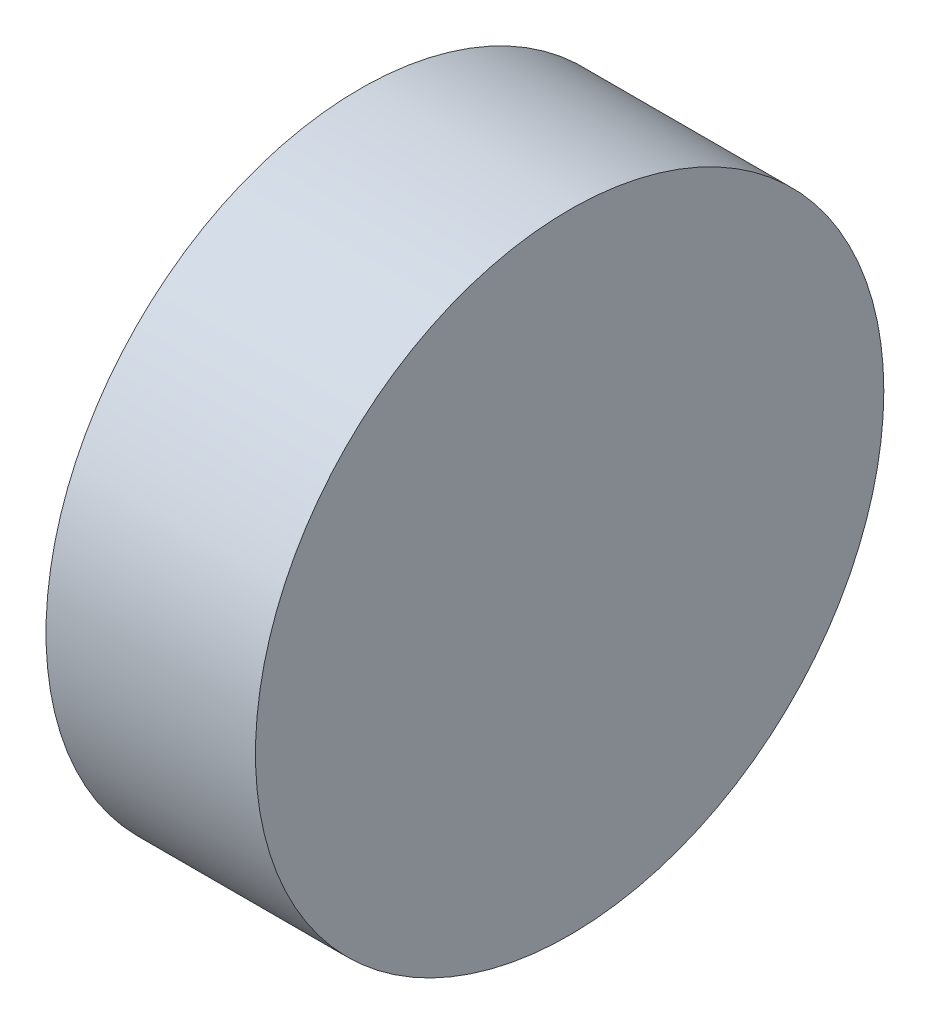
SolidWorks part; units mm, degrees
material "Glass"
ref_plane "Front Plane" through (0, 0, 0) normal (0, 0, 1) x (1, 0, 0)
ref_plane "Top Plane" through (0, 0, 0) normal (0, 1, 0) x (1, 0, 0)
ref_plane "Right Plane" through (0, 0, 0) normal (1, 0, 0) x (0, 0, -1)
sketch "Sketch1" plane through (0, 0, 0) normal (1, 0, 0) x (0, 0, -1)
  circle A0 centre (0, 0) radius 150
  dimension "D1" = 300
extrude "Boss-Extrude1" add sketch "Sketch1" along normal blind 100
